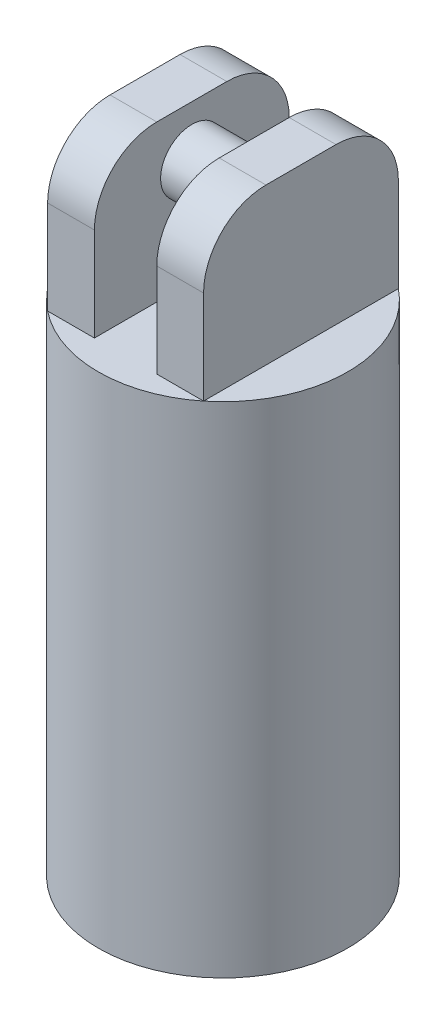
SolidWorks part; units mm, degrees
ref_plane "Front Plane" through (0, 0, 0) normal (0, 0, 1) x (1, 0, 0)
ref_plane "Top Plane" through (0, 0, 0) normal (0, 1, 0) x (1, 0, 0)
ref_plane "Right Plane" through (0, 0, 0) normal (1, 0, 0) x (0, 0, -1)
sketch "Sketch1" plane through (0, 0, 0) normal (0, 1, 0) x (1, 0, 0)
  circle A0 centre (0, 0) radius 50.8
  dimension "D1" = 101.6
extrude "Boss-Extrude1" add sketch "Sketch1" along normal blind 203.2
sketch "Sketch2" plane through (0, 203.2, 0) normal (0, 1, 0) x (1, 0, 0)
  line L1 (-31.75, -39.6557) -> (31.75, -39.6557)
  line L2 (-31.75, -39.6557) -> (-31.75, 39.6557)
  line L3 (-31.75, 39.6557) -> (31.75, 39.6557)
  line L4 (31.75, -39.6557) -> (31.75, 39.6557)
  line L5 (-31.75, -39.6557) -> (31.75, 39.6557) construction
  line L6 (-31.75, 39.6557) -> (31.75, -39.6557) construction
  circle A0 centre (0, 0) radius 50.8 construction
  point P0 (0, 0)
  dimension "D1" = 63.5
extrude "Boss-Extrude2" add sketch "Sketch2" along normal blind 63.5
sketch "Sketch3" plane through (0, 266.7, 0) normal (0, 1, 0) x (1, 0, 0)
  line L0 (31.75, 39.6557) -> (-31.75, 39.6557) construction
  line L1 (-12.7, -39.6557) -> (12.7, -39.6557)
  line L2 (-12.7, -39.6557) -> (-12.7, 39.6557)
  line L3 (-12.7, 39.6557) -> (12.7, 39.6557)
  line L4 (12.7, -39.6557) -> (12.7, 39.6557)
  line L5 (-12.7, -39.6557) -> (12.7, 39.6557) construction
  line L6 (-12.7, 39.6557) -> (12.7, -39.6557) construction
  point P0 (0, 0)
  dimension "D1" = 25.4
extrude "Cut-Extrude1" cut sketch "Sketch3" against normal blind 63.5
fillet "Fillet1" radius 25.4 4 edges at (-22.225, 266.7, -39.6557) (-22.225, 266.7, 39.6557) (22.225, 266.7, -39.6557) (22.225, 266.7, 39.6557)
sketch "Sketch4" plane through (0, 0, 0) normal (0, -1, 0) x (1, 0, 0)
  circle A0 centre (0, 0) radius 31.75
extrude "Cut-Extrude2" cut sketch "Sketch4" against normal blind 63.5
sketch "Sketch5" plane through (31.75, 0, 0) normal (1, 0, 0) x (0, 0, -1)
  circle A0 centre (0, 245.9935) radius 12.7
extrude "Boss-Extrude3" add sketch "Sketch5" against normal blind 53.34
